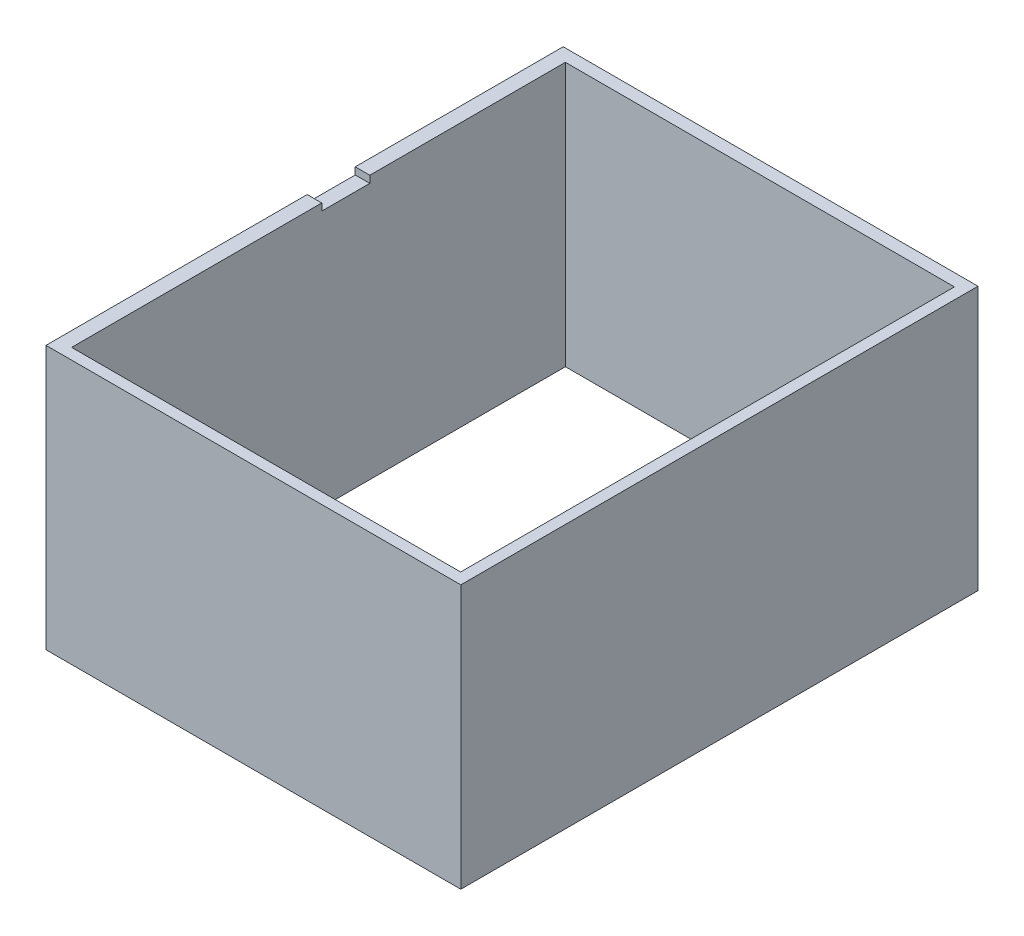
SolidWorks part; units mm, degrees
ref_plane "Front Plane" through (0, 0, 0) normal (0, 0, 1) x (1, 0, 0)
ref_plane "Top Plane" through (0, 0, 0) normal (0, 1, 0) x (1, 0, 0)
ref_plane "Right Plane" through (0, 0, 0) normal (1, 0, 0) x (0, 0, -1)
sketch "Sketch1" plane through (0, 0, 0) normal (0, 1, 0) x (1, 0, 0)
  line L1 (0, 0) -> (5514, 0)
  line L2 (0, 0) -> (0, 6999)
  line L3 (0, 6999) -> (5514, 6999)
  line L4 (5514, 0) -> (5514, 6999)
  line L5 (5672.9475, 7174.3959) -> (-206.5452, 7174.3959)
  line L6 (5672.9475, 7174.3959) -> (5672.9475, -156.5196)
  line L7 (5672.9475, -156.5196) -> (-206.5452, -156.5196)
  line L8 (-206.5452, 7174.3959) -> (-206.5452, -156.5196)
  dimension "D1" = 5514
  dimension "D2" = 6999
extrude "Boss-Extrude1" add sketch "Sketch1" along normal blind 3737
sketch "Sketch2" plane through (0, 3737, 0) normal (0, 1, 0) x (-1, 0, 0)
  line L1 (665.9193, -4226.224) -> (-502.4432, -4226.224)
  line L2 (665.9193, -4226.224) -> (665.9193, -3545.9117)
  line L3 (665.9193, -3545.9117) -> (-502.4432, -3545.9117)
  line L4 (-502.4432, -4226.224) -> (-502.4432, -3545.9117)
extrude "Cut-Extrude1" cut sketch "Sketch2" against normal blind 100
